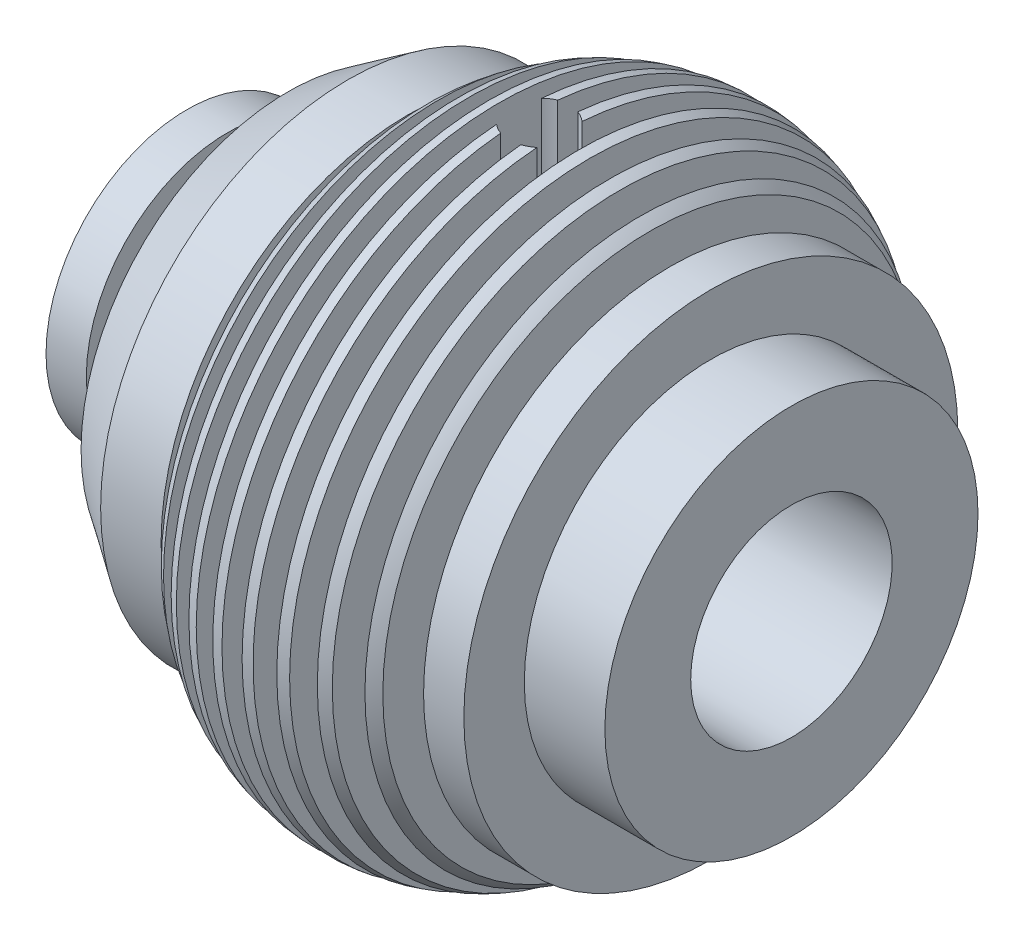
SolidWorks part; units mm, degrees
ref_plane "Front Plane" through (0, 0, 0) normal (0, 0, 1) x (1, 0, 0)
ref_plane "Top Plane" through (0, 0, 0) normal (0, 1, 0) x (1, 0, 0)
ref_plane "Right Plane" through (0, 0, 0) normal (1, 0, 0) x (0, 0, -1)
sketch "Sketch2" plane through (0, 0, 0) normal (0, 0, 1) x (1, 0, 0)
  line L0 (0, 0) -> (3810, 0) construction
  line L2 (0, 381) -> (0, 889)
  line L3 (0, 889) -> (254, 889)
  line L4 (254, 889) -> (254, 635)
  line L5 (254, 635) -> (508, 635)
  line L6 (635, 1303.02) -> (1014.036, 1558.683)
  line L7 (635, 762) -> (635, 1303.02)
  line L8 (1014.036, 1558.683) -> (1395.036, 1558.683)
  line L9 (0, 381) -> (1270, 381)
  line L10 (3810, 635) -> (1270, 635)
  line L11 (1270, 635) -> (1270, 381)
  line L12 (1395.036, 1558.683) -> (1395.036, 1177.683)
  line L13 (3302, 1557.02) -> (3048, 1557.02)
  line L14 (3048, 1557.02) -> (3048, 1176.02)
  line L15 (3302, 1557.02) -> (3302, 1176.02)
  line L16 (3810, 1176.02) -> (3810, 635)
  line L17 (3302, 1176.02) -> (3810, 1176.02)
  line L18 (1395.036, 1177.683) -> (1522.036, 1177.683)
  line L20 (1522.036, 1177.683) -> (1522.036, 1684.4202)
  line L22 (1585.536, 1177.683) -> (1585.536, 1733.8152)
  line L23 (1585.536, 1177.683) -> (1712.536, 1177.683)
  line L24 (1712.536, 1177.683) -> (1712.536, 1812.6086)
  line L26 (1776.036, 1177.683) -> (1776.036, 1843.5967)
  line L27 (1776.036, 1177.683) -> (1903.036, 1177.683)
  line L28 (1903.036, 1177.683) -> (1903.036, 1891.2647)
  line L30 (1966.536, 1177.683) -> (1966.536, 1908.5902)
  line L31 (1966.536, 1177.683) -> (2093.536, 1177.683)
  line L32 (2093.536, 1177.683) -> (2093.536, 1931.2691)
  line L34 (2157.036, 1177.683) -> (2157.036, 1936.8727)
  line L35 (2157.036, 1177.683) -> (2284.036, 1177.683)
  line L36 (2284.036, 1177.683) -> (2284.036, 1936.9045)
  line L38 (2347.536, 1177.683) -> (2347.536, 1931.333)
  line L39 (2347.536, 1177.683) -> (2474.536, 1177.683)
  line L40 (2474.536, 1177.683) -> (2474.536, 1908.7207)
  line L42 (2538.036, 1177.683) -> (2538.036, 1891.4305)
  line L43 (2538.036, 1177.683) -> (2665.036, 1177.683)
  line L44 (2665.036, 1177.683) -> (2665.036, 1843.8399)
  line L46 (2728.536, 1177.683) -> (2728.536, 1812.8956)
  line L47 (2728.536, 1177.683) -> (2855.536, 1177.683)
  line L48 (2855.536, 1177.683) -> (2855.536, 1734.206)
  line L50 (2919.036, 1177.683) -> (2919.036, 1684.8755)
  line L51 (2919.036, 1177.683) -> (3048, 1176.02)
  arc A1 (508, 635) -> (635, 762) centre (508, 762) ccw
  arc A2 (1522.036, 1684.4202) -> (1585.536, 1733.8152) centre (2220.8075, 851.6248) cw
  arc A3 (1712.536, 1812.6086) -> (1776.036, 1843.5967) centre (2220.8075, 851.6248) cw
  arc A4 (1903.036, 1891.2647) -> (1966.536, 1908.5902) centre (2220.8075, 851.6248) cw
  arc A5 (2093.536, 1931.2691) -> (2157.036, 1936.8727) centre (2220.8075, 851.6248) cw
  arc A6 (2284.036, 1936.9045) -> (2347.536, 1931.333) centre (2220.8075, 851.6248) cw
  arc A7 (2474.536, 1908.7207) -> (2538.036, 1891.4305) centre (2220.8075, 851.6248) cw
  arc A8 (2665.036, 1843.8399) -> (2728.536, 1812.8956) centre (2220.8075, 851.6248) cw
  arc A9 (2855.536, 1734.206) -> (2919.036, 1684.8755) centre (2220.8075, 851.6248) cw
  dimension "D5" = 254
  dimension "D6" = 127
  dimension "D9" = 762
  dimension "D17" = 127
  dimension "D1" = 381
  dimension "D2" = 3810
  dimension "D3" = 254
  dimension "D4" = 889
  dimension "D7" = 541.02
  dimension "D8" = 635
  dimension "D10" = 146
  dimension "D11" = 381
  dimension "D12" = 457.2
  dimension "D13" = 508
  dimension "D14" = 254
  dimension "D15" = 922.02
  dimension "D16" = 541.02
revolve "Revolve1" add sketch "Sketch2" angle 360 about L0
sketch "Sketch3" plane through (635, 0, 0) normal (-1, 0, 0) x (0, 0, 1)
  circle A1 centre (0, 1032.51) radius 63.5
  circle A2 centre (1032.51, 0) radius 63.5
  circle A3 centre (0, -1032.51) radius 63.5
  circle A4 centre (-1032.51, 0) radius 63.5
  point P13 (0, 0)
  dimension "D1" = 4
sketch "Sketch6" plane through (0, 0, 0) normal (0, 1, 0) x (1, 0, 0)
  circle A0 centre (2220.536, 0) radius 190.5
extrude "Cut-Extrude1" cut sketch "Sketch6" against normal through all both and the other way through all
extrude "Cut-Extrude2" cut sketch "Sketch3" against normal blind 457.2 contours A4
sketch "Sketch8" plane through (635, 0, 0) normal (-1, 0, 0) x (0, 0, 1)
  circle A0 centre (1032.51, 0) radius 63.5
  circle A1 centre (0, 1032.51) radius 63.5
  circle A2 centre (0, -1032.51) radius 63.5
  circle A3 centre (-1032.51, 0) radius 63.5
  point P11 (0, 0)
  dimension "D1" = 4
extrude "Cut-Extrude3" cut sketch "Sketch8" against normal blind 457.2
